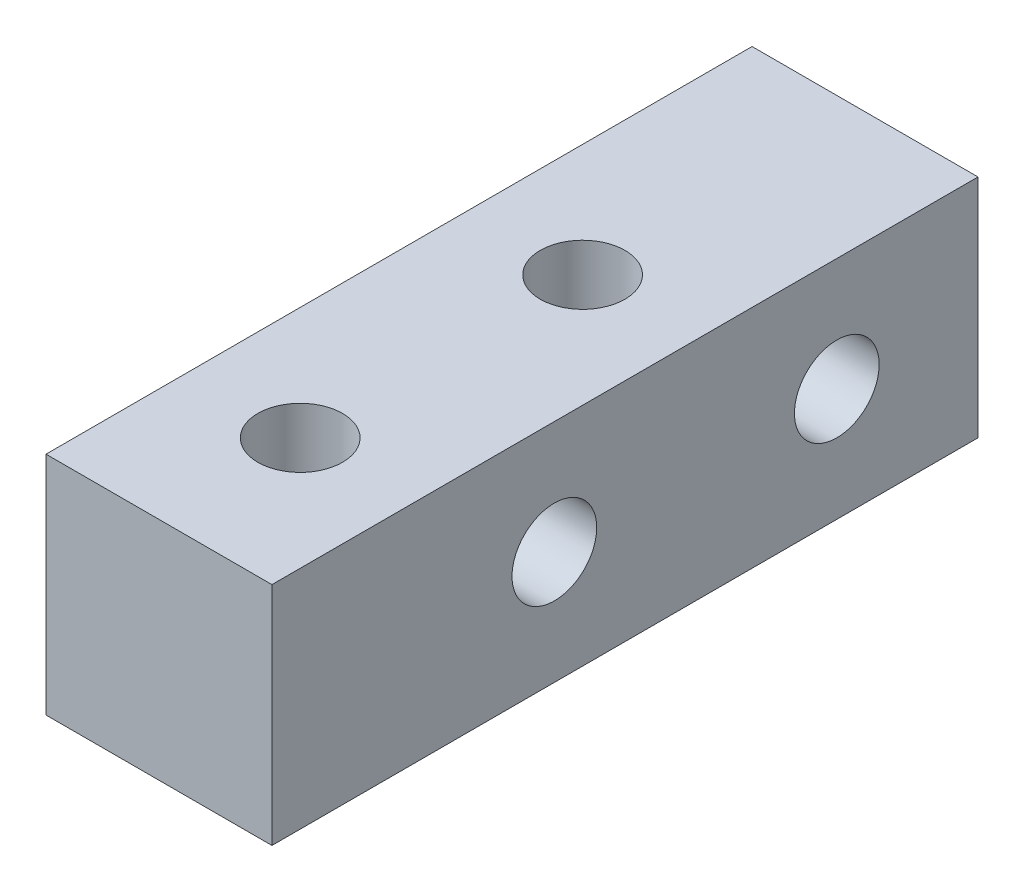
SolidWorks part; units mm, degrees
material "6061-T4 (SS)"
ref_plane "前视基准面" through (0, 0, 0) normal (0, 0, 1) x (1, 0, 0)
ref_plane "上视基准面" through (0, 0, 0) normal (0, 1, 0) x (1, 0, 0)
ref_plane "右视基准面" through (0, 0, 0) normal (1, 0, 0) x (0, 0, -1)
other "Configuration Table"
sketch "草图1" plane through (0, 0, 0) normal (0, 0, 1) x (1, 0, 0)
  line L1 (-4, -4) -> (4, -4)
  line L2 (-4, -4) -> (-4, 4)
  line L3 (-4, 4) -> (4, 4)
  line L4 (4, -4) -> (4, 4)
  line L5 (-4, -4) -> (4, 4) construction
  line L6 (-4, 4) -> (4, -4) construction
  point P0 (0, 0)
  dimension "D1" = 8
extrude "凸台-拉伸1" add sketch "草图1" along normal blind 25
sketch "草图2" plane through (4, 0, 0) normal (1, 0, 0) x (0, 0, -1)
  line L0 (0, 0) -> (-5, 0) construction
  line L1 (-5, 0) -> (-15, 0) construction
  circle A0 centre (-5, 0) radius 1.5
  circle A1 centre (-15, 0) radius 1.5
  dimension "D1" = 3
  dimension "D2" = 5
  dimension "D3" = 10
extrude "切除-拉伸1" cut sketch "草图2" against normal blind 8
sketch "草图3" plane through (0, 4, 0) normal (0, 1, 0) x (1, 0, 0)
  line L0 (0, -25) -> (0, -20) construction
  line L1 (4, -25) -> (-4, -25) construction
  line L2 (0, -20) -> (0, -10) construction
  circle A1 centre (0, -10) radius 1.5
  circle A2 centre (0, -20) radius 1.5
  dimension "D1" = 3
  dimension "D2" = 10
  dimension "D3" = 5
extrude "切除-拉伸2" cut sketch "草图3" against normal blind 8
